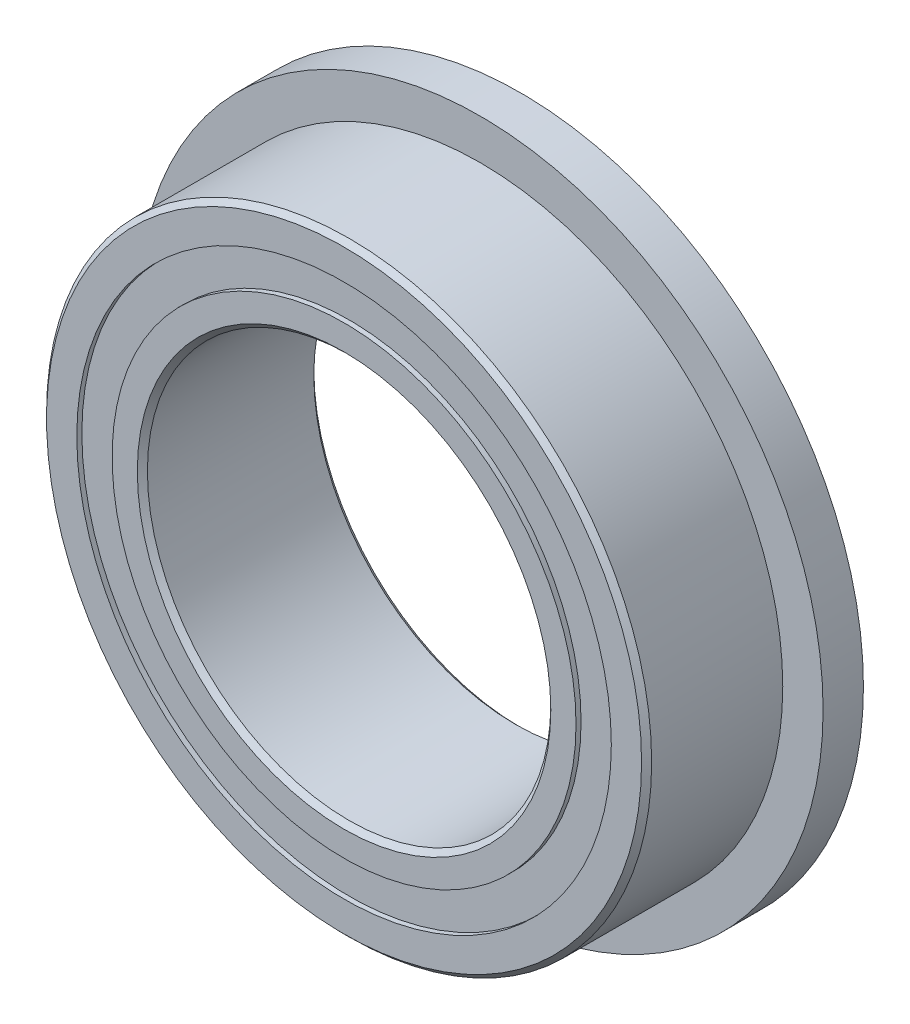
SolidWorks part; units mm, degrees
ref_plane "Front" through (0, 0, 0) normal (0, 0, 1) x (1, 0, 0)
ref_plane "Top" through (0, 0, 0) normal (0, 1, 0) x (1, 0, 0)
ref_plane "Right" through (0, 0, 0) normal (1, 0, 0) x (0, 0, -1)
sketch "Sketch1" plane through (0, 0, 0) normal (0, 1, 0) x (1, 0, 0)
  line L0 (4, -1.65) -> (4.1, -1.75)
  line L1 (4.1, -1.75) -> (4.6, -1.75)
  line L2 (4.6, -1.75) -> (4.6, -1.65)
  line L3 (4.6, -1.65) -> (5.3, -1.65)
  line L4 (5.3, -1.65) -> (5.3, -1.75)
  line L5 (5.3, -1.75) -> (5.9, -1.75)
  line L6 (5.9, -1.75) -> (6, -1.65)
  line L7 (6, -1.65) -> (6, 0.95)
  line L8 (6, 0.95) -> (6.8, 0.95)
  line L9 (6.8, 0.95) -> (6.8, 1.75)
  line L10 (6.8, 1.75) -> (5.3, 1.75)
  line L11 (5.3, 1.75) -> (5.3, 1.65)
  line L12 (5.3, 1.65) -> (4.6, 1.65)
  line L13 (4.6, 1.65) -> (4.6, 1.75)
  line L14 (4.6, 1.75) -> (4.1, 1.75)
  line L15 (4.1, 1.75) -> (4, 1.65)
  line L16 (4, 1.65) -> (4, -1.65)
  line L17 (0, 1.75) -> (0, -1.75) construction
revolve "Revolve1" add sketch "Sketch1" angle 360 about L17
